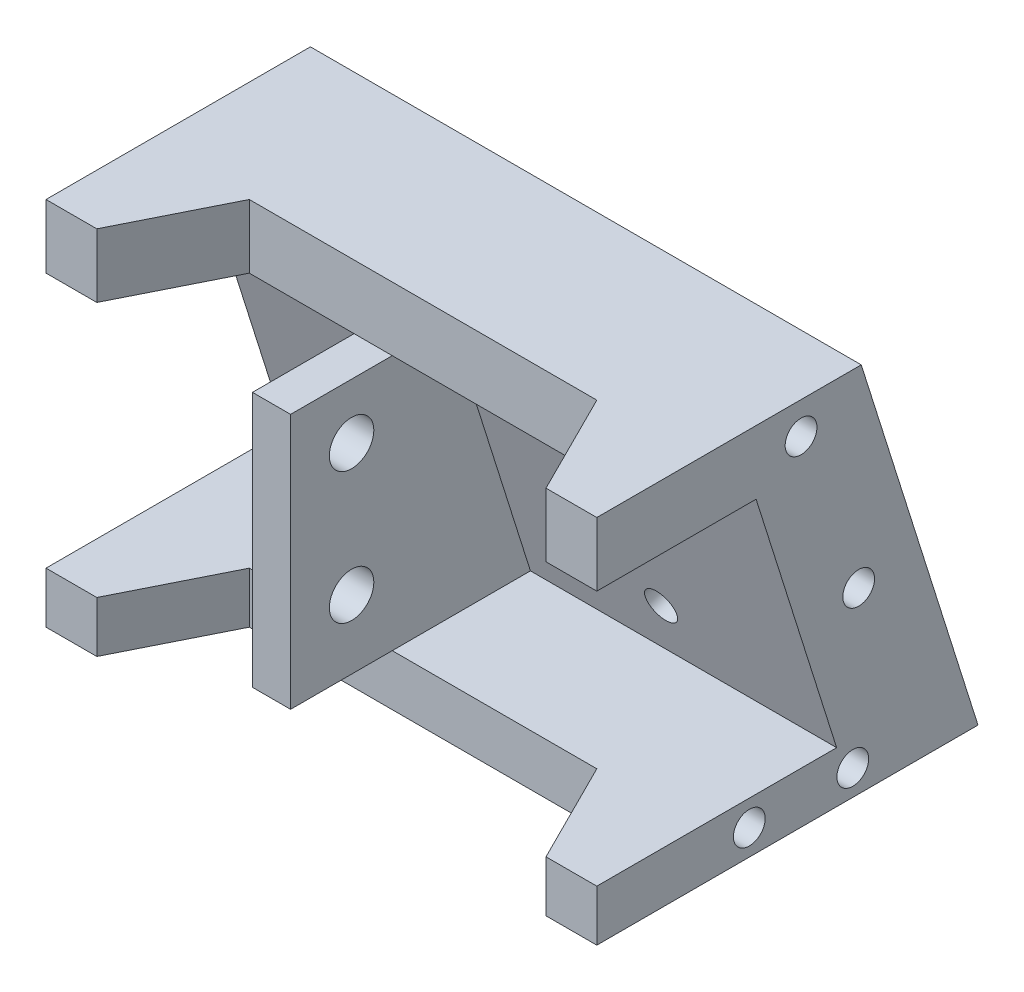
SolidWorks part; units mm, degrees
ref_plane "Front Plane" through (0, 0, 0) normal (0, 0, 1) x (1, 0, 0)
ref_plane "Top Plane" through (0, 0, 0) normal (0, 1, 0) x (1, 0, 0)
ref_plane "Right Plane" through (0, 0, 0) normal (1, 0, 0) x (0, 0, -1)
sketch "Sketch1" plane through (0, 0, 0) normal (0, 0, 1) x (1, 0, 0)
  line L1 (-54.239, -0.1442) -> (-10.889, -0.1442)
  line L2 (-54.239, -0.1442) -> (-54.239, -29.2942)
  line L3 (-54.239, -29.2942) -> (-10.889, -29.2942)
  line L4 (-10.889, -0.1442) -> (-10.889, -29.2942)
extrude "Boss-Extrude1" add sketch "Sketch1" against normal blind 30
sketch "Sketch9" plane through (0, -29.2942, 0) normal (0, -1, 0) x (1, 0, 0)
  line L0 (-10.889, 0) -> (-18.889, 0) construction
  line L1 (-54.239, 0) -> (-10.889, 0) construction
  line L2 (-18.889, 0) -> (-14.889, 0) construction
  line L3 (-14.889, 0) -> (-14.889, -8) construction
  line L5 (-18.889, 0) -> (-18.889, -8) construction
  line L6 (-18.889, -8) -> (-14.889, -8) construction
  line L7 (-14.889, -8) -> (-54.239, -8) construction
  line L8 (-54.239, -30) -> (-54.239, 0) construction
  line L9 (-54.239, -8) -> (-54.239, 0) construction
  line L10 (-54.239, 0) -> (-46.239, 0) construction
  line L11 (-46.239, 0) -> (-46.239, -8) construction
  line L12 (-46.239, -8) -> (-54.239, -8) construction
  line L13 (-54.239, -8) -> (-50.239, -8) construction
  line L14 (-50.239, -8) -> (-50.239, 0) construction
  line L15 (-14.889, 0) -> (-18.889, -8)
  line L16 (-18.889, -8) -> (-46.239, -8)
  line L17 (-46.239, -8) -> (-50.239, 0)
  line L18 (-50.239, 0) -> (-14.889, 0)
extrude "Cut-Extrude6" cut sketch "Sketch9" against normal blind 28.13
sketch "Sketch11" plane through (-54.239, 0, 0) normal (-1, 0, 0) x (0, 0, 1)
  line L0 (0, -29.2942) -> (0, -25.2705) construction
  line L1 (0, -0.1442) -> (0, -29.2942) construction
  line L2 (0, -25.2705) -> (0, -0.1442) construction
  line L3 (0, -0.1442) -> (0, -5.1642) construction
  line L4 (0, -5.1642) -> (0, -25.2705) construction
  line L7 (-30, -0.1442) -> (-30, -29.2942) construction
  line L8 (-30, -5.1642) -> (-30, -29.2942) construction
  line L10 (-30, -29.2942) -> (-30, -25.2705) construction
  line L12 (0, -5.1642) -> (0, -25.2705) construction
  line L13 (-30, -25.2705) -> (-18.8756, -25.2705) construction
  line L14 (0, -25.2705) -> (-18.8756, -25.2705) construction
  line L15 (-18.8756, -25.2705) -> (-18.8756, -5.1642) construction
  line L16 (-18.8756, -5.1642) -> (0, -5.1642) construction
  line L17 (0, -5.1642) -> (0, -25.2705) construction
  line L18 (0, -25.2705) -> (-18.8756, -25.2705)
  line L19 (-18.8756, -25.2705) -> (-18.8756, -5.1642)
  line L20 (-18.8756, -5.1642) -> (0, -5.1642)
  line L21 (0, -5.1642) -> (0, -25.2705)
extrude "Cut-Extrude8" cut sketch "Sketch11" against normal blind 50
sketch "Sketch14" plane through (0, 0, -30) normal (0, 0, -1) x (-1, 0, 0)
  line L0 (10.889, -29.2942) -> (27.139, -29.2942) construction
  line L1 (10.889, -0.1442) -> (27.139, -0.1442) construction
  line L2 (54.239, -29.2942) -> (10.889, -29.2942) construction
  line L4 (10.889, -0.1442) -> (54.239, -0.1442) construction
  line L6 (27.139, -29.2942) -> (27.139, -0.1442) construction
  line L7 (27.139, -0.1442) -> (30.139, -0.1442) construction
  line L8 (30.139, -0.1442) -> (30.139, -29.2942) construction
  line L9 (30.139, -29.2942) -> (27.139, -29.2942) construction
  line L10 (27.139, -29.2942) -> (30.139, -29.2942)
  line L11 (30.139, -29.2942) -> (30.139, -0.1442)
  line L12 (30.139, -0.1442) -> (27.139, -0.1442)
  line L13 (27.139, -0.1442) -> (27.139, -29.2942)
extrude "Boss-Extrude5" add sketch "Sketch14" against normal blind 30
sketch "Sketch15" plane through (-30.139, 0, 0) normal (-1, 0, 0) x (0, 0, 1)
  line L0 (-8, -25.2705) -> (0, -25.2705) construction
  line L1 (0, -29.2942) -> (0, -1.1642) construction
  line L2 (0, -25.2705) -> (0, -29.2942) construction
  line L3 (0, -29.2942) -> (-8, -29.2942) construction
  line L4 (-8, -29.2942) -> (-8, -25.2705) construction
  line L5 (-8, -25.2705) -> (0, -25.2705)
  line L6 (0, -25.2705) -> (0, -29.2942)
  line L7 (0, -29.2942) -> (-8, -29.2942)
  line L8 (-8, -29.2942) -> (-8, -25.2705)
extrude "Cut-Extrude10" cut sketch "Sketch15" against normal blind 5
sketch "Sketch16" plane through (-30.139, 0, 0) normal (-1, 0, 0) x (0, 0, 1)
  line L0 (-8, -1.1642) -> (0, -1.1642) construction
  line L1 (0, -25.2705) -> (0, -1.1642) construction
  line L3 (0, -1.1642) -> (-8, -1.1642) construction
  line L4 (-8, -1.1642) -> (-8, -5.1642) construction
  line L5 (-8, -5.1642) -> (0, -5.1642) construction
  line L6 (0, -5.1642) -> (0, -1.1642) construction
  line L7 (0, -1.1642) -> (0, -5.1642)
  line L8 (0, -5.1642) -> (-8, -5.1642)
  line L9 (-8, -5.1642) -> (-8, -1.1642)
  line L10 (-8, -1.1642) -> (0, -1.1642)
extrude "Cut-Extrude11" cut sketch "Sketch16" against normal blind 5
sketch "Sketch17" plane through (-27.139, 0, 0) normal (-1, 0, 0) x (0, 0, 1)
  line L0 (0, -25.2705) -> (0, -20.4505) construction
  line L3 (0, -5.1642) -> (0, -10.1005) construction
  circle A0 centre (-4.8, -19.8692) radius 1.75
  circle A1 centre (-4.8, -9.5192) radius 1.75
extrude "Cut-Extrude12" cut sketch "Sketch17" against normal blind 3 and the other way blind 4
sketch "Sketch20" plane through (-54.239, 0, 0) normal (-1, 0, 0) x (0, 0, 1)
  line L0 (-30, -0.1442) -> (-30, -29.2942) construction
  line L1 (-30, -29.2942) -> (-20.81, -0.1442) construction
  line L2 (-30, -0.1442) -> (0, -0.1442) construction
  line L3 (-20.81, -0.1442) -> (-30, -0.1442) construction
  line L4 (-30, -29.2942) -> (-30, -0.1442)
  line L5 (-30, -0.1442) -> (-20.81, -0.1442)
  line L6 (-20.81, -0.1442) -> (-30, -29.2942)
extrude "Cut-Extrude14" cut sketch "Sketch20" against normal blind 50
sketch "Sketch30" plane through (-54.239, 0, 0) normal (-1, 0, 0) x (0, 0, 1)
  line L0 (-25.1458, -29.2942) -> (-7, -29.2942) construction
  line L1 (-7, -29.2942) -> (-12.0012, -29.2942) construction
  line L2 (-12.0012, -29.2942) -> (-25.1458, -29.2942) construction
  line L3 (-25.1458, -29.2942) -> (-20.1458, -29.2942) construction
  line L4 (-7, -29.2942) -> (-7, -27.2842) construction
  line L5 (-7, -27.2842) -> (-20.1458, -27.2842) construction
  line L6 (-20.1458, -27.2842) -> (-7, -27.2842) construction
  line L7 (-7, -27.2842) -> (-12.0012, -27.2842) construction
  line L8 (-20.1458, -29.2942) -> (-20.1458, -27.2842) construction
  line L10 (0, -25.2705) -> (0, -29.2942) construction
  line L11 (0, -27.2823) -> (0, -29.2942) construction
  line L12 (0, -29.2942) -> (0, -27.2823) construction
  line L13 (0, -27.2823) -> (-7, -27.2842) construction
  line L14 (-7, -27.2842) -> (-7, -29.2942) construction
  line L15 (-7, -29.2942) -> (-7, -27.2842) construction
  line L16 (-7, -27.2842) -> (-12.0012, -27.2842) construction
  line L17 (-12.0012, -27.2842) -> (-12.0012, -29.2942) construction
  line L18 (-12.0012, -29.2942) -> (-12.0012, -27.2842) construction
  circle A0 centre (-12.0012, -27.2842) radius 1.25
  circle A1 centre (-20.1458, -27.2842) radius 1.25
extrude "Cut-Extrude23" cut sketch "Sketch30" against normal blind 45
sketch "Sketch31" plane through (-54.239, 0, 0) normal (-1, 0, 0) x (0, 0, 1)
  line L0 (-20.1458, -27.2842) -> (-12.0012, -27.2842) construction
  line L1 (-12.0012, -27.2842) -> (-16.0735, -27.2842) construction
  line L2 (-16.0735, -27.2842) -> (-16.0735, -0.1442) construction
  line L3 (-16.0735, -5.1642) -> (-16.0735, -0.1442) construction
  line L4 (-16.0735, -0.1442) -> (-16.0735, -5.1642) construction
  line L5 (0, -5.1642) -> (-18.8756, -5.1642) construction
  line L6 (-16.0735, -5.1642) -> (-16.0735, -2.6542) construction
  line L7 (-20.81, -0.1442) -> (0, -0.1442) construction
  line L8 (-16.0735, -0.1442) -> (-16.0735, -2.6542) construction
  line L9 (-16.0735, -2.6542) -> (-16.0735, -0.1442) construction
  line L10 (-16.0735, -0.1442) -> (-16.0735, -2.6542) construction
  circle A0 centre (-16.0735, -2.6542) radius 1.25
extrude "Cut-Extrude24" cut sketch "Sketch31" against normal blind 50
sketch "Sketch32" plane through (-54.239, 0, 0) normal (-1, 0, 0) x (0, 0, 1)
  line L0 (-25.1427, -28.8998) -> (-22.7033, -1.5865) construction
  line L1 (-22.7033, -1.5865) -> (-23.923, -15.2431) construction
  line L2 (-23.923, -15.2431) -> (-20.6098, -15.2431) construction
  circle A0 centre (-20.6098, -15.2431) radius 1.25
extrude "Cut-Extrude25" cut sketch "Sketch32" against normal blind 50
sketch "Sketch56" plane through (0, -1.1642, 0) normal (0, -1, 0) x (1, 0, 0)
  line L0 (-14.889, 0) -> (-18.889, -8)
  line L1 (-18.889, -8) -> (-46.239, -8)
  line L2 (-46.239, -8) -> (-50.239, 0)
  line L3 (-50.239, 0) -> (-14.889, 0)
extrude "Cut-Extrude29" cut sketch "Sketch56" against normal blind 5
sketch "Sketch68" plane through (-27.139, 0, 0) normal (1, 0, 0) x (0, 0, -1)
  line L0 (18.8756, -5.1642) -> (12.5356, -5.1642)
  line L1 (8, -5.1642) -> (18.8756, -5.1642) construction
  line L2 (12.5356, -5.1642) -> (18.8756, -25.2705)
  line L4 (18.8756, -5.1642) -> (18.8756, -25.2705)
extrude "Boss-Extrude13" add sketch "Sketch68" along normal blind 16.25
sketch "Sketch73" plane through (-30.139, 0, 0) normal (-1, 0, 0) x (0, 0, 1)
  line L0 (-18.8756, -5.1642) -> (-12.5356, -5.1642)
  line L1 (-12.5356, -5.1642) -> (-18.8756, -25.2705)
  line L2 (-18.8756, -25.2705) -> (-18.8756, -5.1642)
extrude "Boss-Extrude14" add sketch "Sketch73" along normal blind 24.1
mirror "Mirror1" about plane through (-10.889, -0.1442, -30) normal (1, 0, 0) of bodies 154 157
delete or keep bodies "Body-Delete/Keep 1" type delete bodies bodies 154
sketch "Sketch74" plane through (0, 5.9545, -18.8873) normal (0, 0.3007, -0.9537) x (-1, 0, 0)
  circle A0 centre (-1.5344, -25.5466) radius 1.25
  circle A1 centre (-19.9154, -25.5466) radius 1.25
  circle A2 centre (-19.9154, -14.283) radius 1.25
  circle A3 centre (-1.5344, -14.283) radius 1.25
extrude "Cut-Extrude30" cut sketch "Sketch74" against normal blind 10 contours A0 | A1 | A2 | A3
